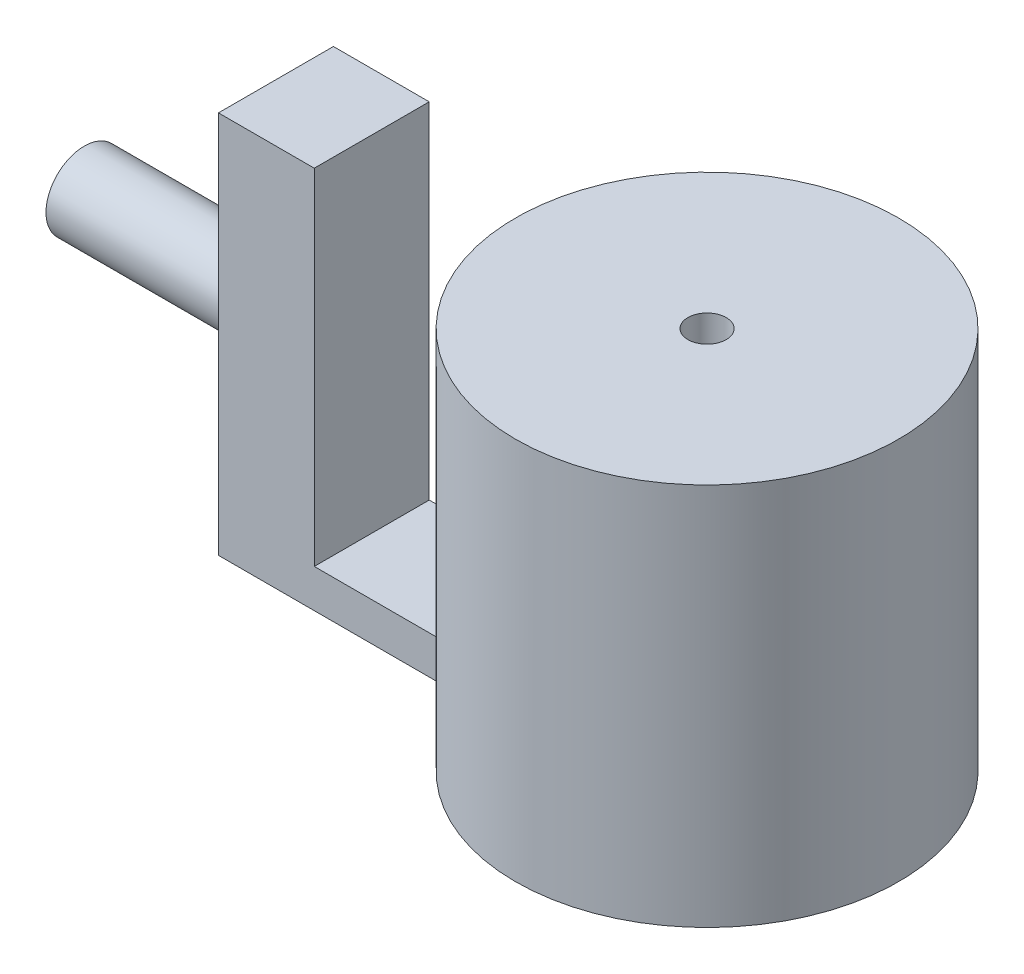
SolidWorks part; units mm, degrees
ref_plane "Front Plane" through (0, 0, 0) normal (0, 0, 1) x (1, 0, 0)
ref_plane "Top Plane" through (0, 0, 0) normal (0, 1, 0) x (1, 0, 0)
ref_plane "Right Plane" through (0, 0, 0) normal (1, 0, 0) x (0, 0, -1)
sketch "Sketch2" plane through (0, 0, 0) normal (0, 1, 0) x (1, 0, 0)
  circle A0 centre (0, 0) radius 50
  circle A1 centre (0, 0) radius 5
  dimension "D1" = 100
  dimension "D2" = 10
extrude "Boss-Extrude1" add sketch "Sketch2" along normal blind 100
sketch "Sketch3" plane through (0, 0, 0) normal (0, -1, 0) x (1, 0, 0)
  line L0 (-100, 0) -> (0, 0) construction
  line L1 (-47.697, -15) -> (-100, -15)
  line L3 (-47.697, 15) -> (-100, 15)
  line L4 (-100, -15) -> (-100, 15)
  line L5 (-50, 0) -> (-100, 15) construction
  line L6 (-50, 0) -> (-100, -15) construction
  circle A0 centre (0, 0) radius 50 construction
  arc A1 (-47.697, -15) -> (-47.697, 15) centre (0, 0) cw
  point P0 (-50, 0)
  dimension "D1" = 30
  dimension "D2" = 100
extrude "Boss-Extrude2" add sketch "Sketch3" against normal blind 10
sketch "Sketch4" plane through (0, 0, 0) normal (0, -1, 0) x (1, 0, 0)
  line L1 (-100, 15) -> (-100, -15) construction
  line L2 (-112.5, 15) -> (-87.5, 15)
  line L3 (-112.5, 15) -> (-112.5, -15)
  line L4 (-112.5, -15) -> (-87.5, -15)
  line L5 (-87.5, 15) -> (-87.5, -15)
  line L6 (-112.5, 15) -> (-87.5, -15) construction
  line L7 (-112.5, -15) -> (-87.5, 15) construction
  line L8 (-100, -15) -> (-47.697, -15) construction
  point P0 (-100, 0)
  dimension "25" = 25
extrude "Boss-Extrude3" add sketch "Sketch4" against normal up to surface (100 mm away) up to face at (0, 100, 50)
sketch "Sketch5" plane through (-112.5, 0, 0) normal (-1, 0, 0) x (0, 0, 1)
  line L0 (0, 0) -> (0, 50) construction
  circle A0 centre (0, 50) radius 10
  dimension "D2" = 20
  dimension "D1" = 50
extrude "Boss-Extrude4" add sketch "Sketch5" along normal blind 50
